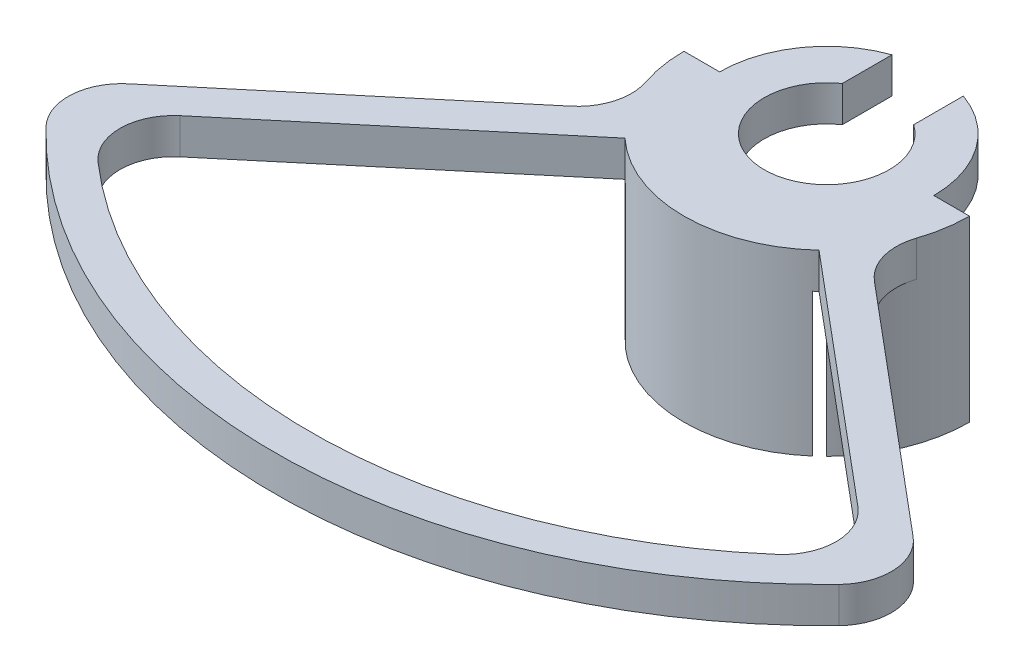
SolidWorks part; units mm, degrees
material "PE Low/Medium Density"
ref_plane "Front Plane" through (0, 0, 0) normal (0, 0, 1) x (1, 0, 0)
ref_plane "Top Plane" through (0, 0, 0) normal (0, 1, 0) x (1, 0, 0)
ref_plane "Right Plane" through (0, 0, 0) normal (1, 0, 0) x (0, 0, -1)
sketch "Sketch1" plane through (0, 0, 0) normal (0, 1, 0) x (1, 0, 0)
  line L0 (-2, 2.8723) -> (-2, 5.6569)
  line L1 (2, 2.8723) -> (2, 5.6569)
  line L3 (0, 21.274) -> (0, -56.7596) construction
  line L8 (21.5082, -19.3529) -> (3.8892, -4.5688)
  line L9 (24.3259, -19.1064) -> (5.1748, -3.0367)
  line L13 (0, 0) -> (-34.0698, -28.588) construction
  line L14 (0, 0) -> (29.9546, -25.1349) construction
  line L15 (-24.3259, -19.1064) -> (-5.1748, -3.0367)
  line L16 (-21.5082, -19.3529) -> (-3.8892, -4.5688)
  arc A0 (-2, 5.6569) -> (-4.9039, 3.4571) centre (0, 0) ccw
  arc A1 (2, 2.8723) -> (-2, 2.8723) centre (0, 0) cw
  arc A4 (-4.9039, 3.4571) -> (-5.1748, -3.0367) centre (0, 0) ccw
  arc A6 (-1, -5.9161) -> (3.8892, -4.5688) centre (0, 0) ccw
  arc A7 (3.4952, 4.8768) -> (2, 5.6569) centre (0, 0) ccw
  arc A8 (-24.3259, -19.1064) -> (24.3259, -19.1064) centre (0, 0) ccw
  arc A9 (-21.5082, -19.3529) -> (21.5082, -19.3529) centre (0, 0) ccw
  arc A10 (-3.8892, -4.5688) -> (-1, -5.9161) centre (0, 0) ccw
  arc A11 (5.1748, -3.0367) -> (3.4952, 4.8768) centre (0, 0) ccw
  dimension "D1" = 6
  dimension "D3" = 3.5
  dimension "D4" = 2
  dimension "D5" = 25
  dimension "D2" = 4
  dimension "D9" = 100
  dimension "D11" = 23
extrude "Boss-Extrude1" add sketch "Sketch1" along normal blind 2
sketch "Sketch2" plane through (0, 0, 0) normal (0, 1, 0) x (1, 0, 0)
  line L0 (-1.1, 0) -> (1.1, 0) construction
  line L1 (-44.1375, 0) -> (50.1466, 0) construction
  line L2 (-8, 0) -> (-5.9, 0)
  line L3 (8, 0) -> (5.9, 0)
  line L4 (0, -1.1) -> (0, 1.1) construction
  line L5 (-4.2899, -4.0505) -> (-5.6539, -5.6598)
  line L6 (3.7414, -4.562) -> (5.2516, -6.0349)
  line L7 (4.2899, -4.0505) -> (5.6539, -5.6598)
  line L8 (0, 0) -> (7.6547, -8.2087) construction
  line L9 (-3.7414, -4.562) -> (-5.2516, -6.0349)
  arc A0 (-8, 0) -> (-5.6539, -5.6598) centre (0, 0) ccw
  arc A1 (-5.9, 0) -> (-4.2899, -4.0505) centre (0, 0) ccw
  arc A2 (-3.7414, -4.562) -> (3.7414, -4.562) centre (0, 0) ccw
  arc A3 (-5.2516, -6.0349) -> (5.2516, -6.0349) centre (0, 0) ccw
  arc A4 (4.2899, -4.0505) -> (5.9, 0) centre (0, 0) ccw
  arc A5 (5.6539, -5.6598) -> (8, 0) centre (0, 0) ccw
  dimension "D1" = 8
  dimension "D2" = 2.1
  dimension "D5" = 0.75
  dimension "D3" = 0.55
  dimension "D4" = 47
extrude "Boss-Extrude2" add sketch "Sketch2" against normal blind 8 and the other way up to surface other way up to face at (0, 2, 5.4912)
sketch "Sketch3" plane through (0, 0, 0) normal (0, 1, 0) x (1, 0, 0)
  line L0 (-1.1, 0) -> (1.1, 0) construction
  line L1 (-8, 0) -> (-5.9032, 0)
  line L2 (5.9032, 0) -> (8, 0)
  arc A0 (-8, 0) -> (8, 0) centre (0, 0) ccw
  arc A1 (-8, 0) -> (-6.7231, -4.3359) centre (0, 0) ccw construction
  arc A2 (6.7231, -4.3359) -> (8, 0) centre (0, 0) ccw construction
  arc A3 (-5.9032, 0) -> (5.9032, 0) centre (0, 0) ccw
extrude "Boss-Extrude3" add sketch "Sketch3" along normal up to surface (2 mm away) up to face at (0, 2, 10.0905)
fillet "Fillet1" radius 3 6 edges at (-6.7231, 1, 4.3359) (6.7231, 1, 4.3359) (24.3259, 1, 19.1064) (-24.3259, 1, 19.1064) (-21.5082, 1, 19.3529) (21.5082, 1, 19.3529)
